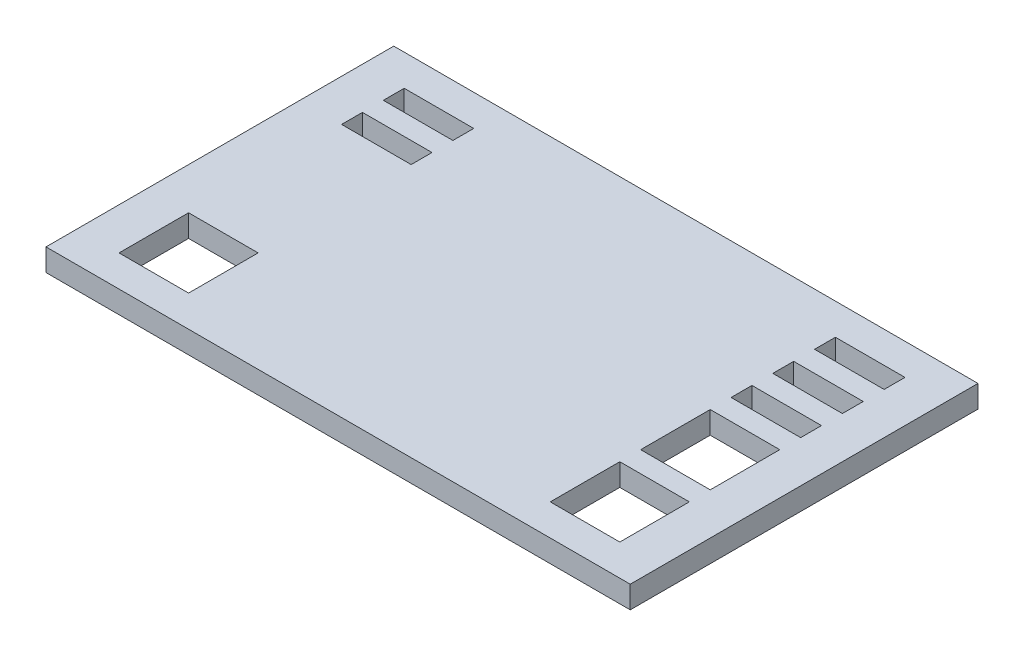
SolidWorks part; units mm, degrees
ref_plane "Front Plane" through (0, 0, 0) normal (0, 0, 1) x (1, 0, 0)
ref_plane "Top Plane" through (0, 0, 0) normal (0, 1, 0) x (1, 0, 0)
ref_plane "Right Plane" through (0, 0, 0) normal (1, 0, 0) x (0, 0, -1)
sketch "Sketch1" plane through (0, 0, 0) normal (0, 1, 0) x (1, 0, 0)
  line L0 (-24, 0) -> (24, 0) construction
  line L1 (-24, -12.5) -> (24, -12.5)
  line L2 (-24, -12.5) -> (-24, 12.5)
  line L3 (-24, 12.5) -> (24, 12.5)
  line L4 (24, -12.5) -> (24, 12.5)
  line L5 (-24, -12.5) -> (24, 12.5) construction
  line L6 (-24, 12.5) -> (24, -12.5) construction
  line L7 (13, 3.5) -> (18, 3.5) construction
  line L8 (13, 4.25) -> (18, 4.25)
  line L9 (13, 4.25) -> (13, 2.75)
  line L10 (13, 2.75) -> (18, 2.75)
  line L11 (18, 4.25) -> (18, 2.75)
  line L12 (13, 1.25) -> (18, 1.25)
  line L13 (13, 1.25) -> (13, -3.75)
  line L14 (13, -3.75) -> (18, -3.75)
  line L15 (18, 1.25) -> (18, -3.75)
  line L16 (13, -1.25) -> (18, -1.25) construction
  line L17 (0, 12.5) -> (0, -12.5) construction
  line L18 (10, 12.5) -> (10, -12.5) construction
  line L19 (21, 12.5) -> (21, -12.5) construction
  line L20 (-18, 10.25) -> (-18, 8.75)
  line L21 (13, 10.25) -> (18, 10.25)
  line L22 (13, 10.25) -> (13, 8.75)
  line L23 (13, 8.75) -> (18, 8.75)
  line L24 (18, 10.25) -> (18, 8.75)
  line L25 (13, 9.5) -> (18, 9.5) construction
  line L26 (-13, 8.75) -> (-18, 8.75)
  line L27 (-13, 10.25) -> (-18, 10.25)
  line L28 (-13, 10.25) -> (-13, 8.75)
  line L29 (13, 6.5) -> (18, 6.5) construction
  line L30 (13, 7.25) -> (18, 7.25)
  line L31 (13, 7.25) -> (13, 5.75)
  line L32 (13, 5.75) -> (18, 5.75)
  line L33 (18, 7.25) -> (18, 5.75)
  line L34 (13, -7.75) -> (18, -7.75) construction
  line L35 (13, -5.25) -> (18, -5.25)
  line L36 (13, -5.25) -> (13, -10.25)
  line L37 (13, -10.25) -> (18, -10.25)
  line L38 (18, -5.25) -> (18, -10.25)
  line L39 (-18, -5.25) -> (-18, -10.25)
  line L40 (-13, -5.25) -> (-18, -5.25)
  line L41 (-13, -5.25) -> (-13, -10.25)
  line L42 (-13, 5.75) -> (-18, 5.75)
  line L43 (-13, 7.25) -> (-18, 7.25)
  line L44 (-13, 7.25) -> (-13, 5.75)
  line L45 (-18, 7.25) -> (-18, 5.75)
  line L46 (-13, -10.25) -> (-18, -10.25)
  circle A0 centre (21, 0) radius 1 construction
  circle A1 centre (0, 0) radius 1 construction
  circle A3 centre (-21, 0) radius 1 construction
  point P0 (0, 0)
  dimension "D9" = 2
  dimension "D11" = 2
  dimension "D13" = 1.5
  dimension "D1" = 25
  dimension "D2" = 1.5
  dimension "D3" = 5
  dimension "D4" = 5
  dimension "D5" = 5
  dimension "D6" = 1.5
  dimension "D7" = 10
  dimension "D8" = 3
  dimension "D10" = 3
  dimension "D12" = 5
  dimension "D14" = 1.5
  dimension "D15" = 5
  dimension "D16" = 1.5
  dimension "D17" = 5
  dimension "D18" = 5
  dimension "D19" = 1.5
  dimension "D20" = 1.5
  dimension "D21" = 2.25
extrude "Boss-Extrude1" add sketch "Sketch1" along normal blind 1.6 contours L1 L4 L3 L2 L27 L28 L26 L20 L21 L24 L23 L22 L12 L15 L14 L13 L8 L11 L10 L9 A0 A3
sketch "Sketch2" plane through (0, 1.6, 0) normal (0, 1, 0) x (1, 0, 0)
  line L0 (13.6251, -1.2968) -> (16.5251, -1.2968)
  line L1 (13.6251, 4.7032) -> (16.5251, 4.7032)
  line L2 (13.6251, 4.7032) -> (13.6251, 3.7032)
  line L3 (13.6251, 3.7032) -> (16.5251, 3.7032)
  line L4 (16.5251, 4.7032) -> (16.5251, 3.7032)
  line L5 (13.6251, 4.7032) -> (16.5251, 3.7032) construction
  line L6 (13.6251, 3.7032) -> (16.5251, 4.7032) construction
  line L7 (13.6251, -3.9468) -> (17.6251, -3.9468)
  line L8 (13.6251, -3.9468) -> (13.6251, -5.6468)
  line L9 (13.6251, -5.6468) -> (17.6251, -5.6468)
  line L10 (17.6251, -3.9468) -> (17.6251, -5.6468)
  line L11 (13.6251, -3.9468) -> (17.6251, -5.6468) construction
  line L12 (13.6251, -5.6468) -> (17.6251, -3.9468) construction
  line L13 (13.6251, -1.2968) -> (13.6251, -2.2968)
  line L14 (13.6251, -2.2968) -> (16.5251, -2.2968)
  line L15 (16.5251, -1.2968) -> (16.5251, -2.2968)
  line L16 (13.6251, -1.2968) -> (16.5251, -2.2968) construction
  line L17 (13.6251, -2.2968) -> (16.5251, -1.2968) construction
  line L18 (13.6251, -6.9468) -> (17.6251, -6.9468)
  line L19 (13.6251, -6.9468) -> (13.6251, -8.6468)
  line L20 (13.6251, -8.6468) -> (17.6251, -8.6468)
  line L21 (17.6251, -6.9468) -> (17.6251, -8.6468)
  line L22 (13.6251, -6.9468) -> (17.6251, -8.6468) construction
  line L23 (13.6251, -8.6468) -> (17.6251, -6.9468) construction
  line L24 (13.6251, 1.7032) -> (16.5251, 1.7032)
  line L25 (13.6251, 1.7032) -> (13.6251, 0.7032)
  line L26 (13.6251, 0.7032) -> (16.5251, 0.7032)
  line L27 (16.5251, 1.7032) -> (16.5251, 0.7032)
  line L28 (13.6251, 1.7032) -> (16.5251, 0.7032) construction
  line L29 (13.6251, 0.7032) -> (16.5251, 1.7032) construction
  point P0 (15.0751, 4.2032)
  point P5 (15.6251, -4.7968)
  point P10 (15.0751, -1.7968)
  point P15 (15.6251, -7.7968)
  point P20 (15.0751, 1.2032)
other "AlignGroup1" parameters "D1"=8.4493, "D2"=22.4988, "D3"=22.99, "D4"=35.4675, "D5"=1, "D6"=2.9, "D7"=1.7, "D8"=4, "D9"=1, "D10"=2.9, "D11"=0, "D12"=3, "D13"=5.5716, "D14"=6, "D15"=9, "D16"=12
sketch "Sketch3" plane through (0, 0, 0) normal (0, -1, 0) x (1, 0, 0)
  line L0 (0, 0) -> (0, -5) construction
  circle A0 centre (0, 0) radius 1
  circle A1 centre (0, -5) radius 1
  dimension "D1" = 2
  dimension "D2" = 2
  dimension "D3" = 5
extrude "Boss-Extrude2" add sketch "Sketch3" along normal blind 0.5
sketch "Sketch4" plane through (0, -0.5, 0) normal (0, -1, 0) x (1, 0, 0)
  circle A0 centre (0, 0) radius 0.75
  circle A1 centre (0, -5) radius 0.75
  dimension "D1" = 1.5
  dimension "D2" = 1.5
extrude "Boss-Extrude3" add sketch "Sketch4" along normal blind 4.5
sketch "Sketch5" plane through (0, -5, 0) normal (0, -1, 0) x (1, 0, 0)
  circle A0 centre (0, 0) radius 0.45
  circle A1 centre (0, -5) radius 0.45
  dimension "D1" = 0.9
  dimension "D2" = 0.9
extrude "Boss-Extrude4" add sketch "Sketch5" along normal blind 2
fillet "Fillet1" radius 0.45 2 edges at (0, -7, -0.45) (0, -7, -5.45)
sketch "Sketch6" plane through (0, 0, 0) normal (0, -1, 0) x (1, 0, 0)
  line L0 (-24, 12.5) -> (-24, -12.5)
  line L1 (-24, 12.5) -> (-21, 12.5)
  line L2 (-24, -12.5) -> (-21, -12.5)
  line L3 (-21, 12.5) -> (-21, -12.5)
  line L4 (24, 12.5) -> (24, -12.5)
  line L5 (24, 12.5) -> (21, 12.5)
  line L6 (24, -12.5) -> (21, -12.5)
  line L7 (21, 12.5) -> (21, -12.5)
  dimension "D1" = 3
  dimension "D2" = 3
extrude "Cut-Extrude1" cut sketch "Sketch6" against normal blind 10
